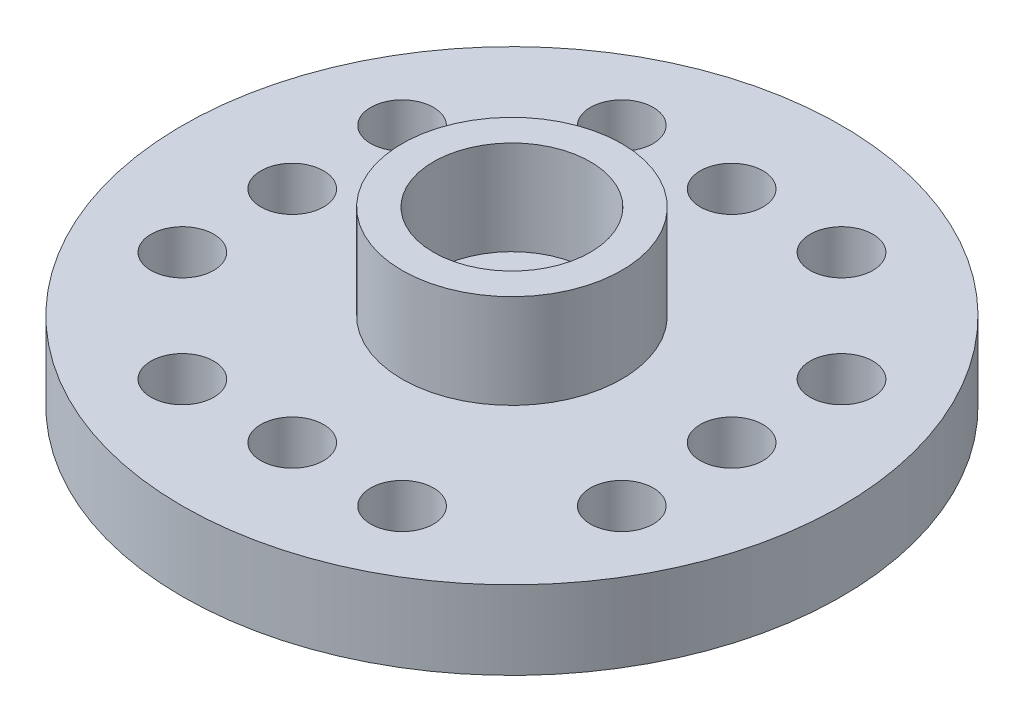
SolidWorks part; units mm, degrees
ref_plane "Front Plane" through (0, 0, 0) normal (0, 0, 1) x (1, 0, 0)
ref_plane "Top Plane" through (0, 0, 0) normal (0, 1, 0) x (1, 0, 0)
ref_plane "Right Plane" through (0, 0, 0) normal (1, 0, 0) x (0, 0, -1)
sketch "Sketch1" plane through (0, 0, 0) normal (0, 1, 0) x (1, 0, 0)
  circle A0 centre (0, 0) radius 10.5
  dimension "D1" = 21
extrude "Boss-Extrude1" add sketch "Sketch1" along normal blind 2.5
sketch "Sketch2" plane through (0, 2.5, 0) normal (0, 1, 0) x (1, 0, 0)
  circle A0 centre (0, 0) radius 2.5
  circle A1 centre (0, 0) radius 3.5
  dimension "D1" = 5
  dimension "D2" = 1
extrude "Boss-Extrude2" add sketch "Sketch2" along normal blind 3
sketch "Sketch3" plane through (0, 2.5, 0) normal (0, 1, 0) x (1, 0, 0)
  circle A0 centre (0, 0) radius 1.5
  dimension "D1" = 3
extrude "Cut-Extrude1" cut sketch "Sketch3" against normal blind 3
sketch "Sketch4" plane through (0, 0, 0) normal (0, -1, 0) x (1, 0, 0)
  circle A0 centre (0, 0) radius 1.5
  circle A1 centre (0, 0) radius 4.5
  dimension "D1" = 3
  dimension "D2" = 3
extrude "Cut-Extrude2" cut sketch "Sketch4" against normal blind 1.5
sketch "Sketch5" plane through (0, 0, 0) normal (0, -1, 0) x (1, 0, 0)
  line L0 (-3.5, 7) -> (3.5, 7) construction
  circle A0 centre (0, 7) radius 1
  circle A1 centre (3.5, 7) radius 1
  circle A2 centre (-3.5, 7) radius 1
  circle A3 centre (7, 3.5) radius 1
  circle A4 centre (7, 0) radius 1
  circle A5 centre (7, -3.5) radius 1
  circle A6 centre (3.5, -7) radius 1
  circle A7 centre (0, -7) radius 1
  circle A8 centre (-3.5, -7) radius 1
  circle A9 centre (-7, -3.5) radius 1
  circle A10 centre (-7, 0) radius 1
  circle A11 centre (-7, 3.5) radius 1
  point P9 (0, 7)
  point P29 (0, 0)
  dimension "D1" = 2
  dimension "D2" = 7
  dimension "D3" = 7
  dimension "D4" = 4
extrude "Cut-Extrude3" cut sketch "Sketch5" against normal blind 3
